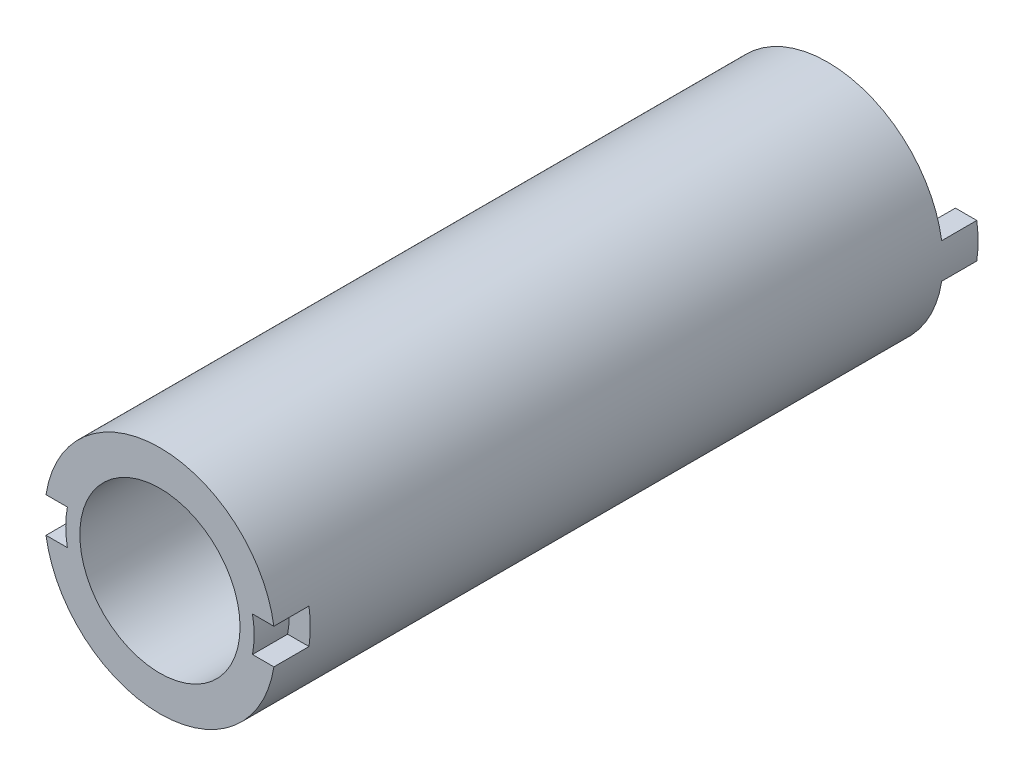
SolidWorks part; units mm, degrees
ref_plane "Front Plane" through (0, 0, 0) normal (0, 0, 1) x (1, 0, 0)
ref_plane "Top Plane" through (0, 0, 0) normal (0, 1, 0) x (1, 0, 0)
ref_plane "Right Plane" through (0, 0, 0) normal (1, 0, 0) x (0, 0, -1)
sketch "Sketch1" plane through (0, 0, 0) normal (0, 0, 1) x (1, 0, 0)
  circle A0 centre (0, 0) radius 11.4
  circle A1 centre (0, 0) radius 16.4
  dimension "D1" = 22.8
  dimension "D2" = 5
extrude "Boss-Extrude1" add sketch "Sketch1" along normal blind 95
sketch "Sketch3" plane through (0, 0, 0) normal (0, 0, -1) x (-1, 0, 0)
  line L0 (13.1647, 2.5) -> (16.2083, 2.5)
  line L1 (-16.2083, 2.5) -> (-13.1647, 2.5)
  line L3 (-16.2083, -2.5) -> (-13.1647, -2.5)
  line L5 (13.1647, -2.5) -> (16.2083, -2.5)
  line L6 (-16.4, 0) -> (-13.4, 0) construction
  arc A0 (-16.2083, 2.5) -> (-16.2083, -2.5) centre (0, 0) ccw
  arc A1 (-13.1647, 2.5) -> (-13.1647, -2.5) centre (0, 0) ccw
  arc A2 (16.2083, -2.5) -> (16.2083, 2.5) centre (0, 0) ccw
  arc A3 (13.1647, -2.5) -> (13.1647, 2.5) centre (0, 0) ccw
  circle A4 centre (0, 0) radius 16.4 construction
  dimension "D1" = 5
  dimension "D2" = 3
extrude "Boss-Extrude2" add sketch "Sketch3" along normal blind 5
sketch "Sketch4" plane through (0, 0, 95) normal (0, 0, 1) x (1, 0, 0)
  line L0 (13.1647, 2.5) -> (16.2083, 2.5)
  line L1 (-16.2083, 2.5) -> (-13.1647, 2.5)
  line L3 (-16.2083, -2.5) -> (-13.1647, -2.5)
  line L5 (13.1647, -2.5) -> (16.2083, -2.5)
  line L6 (-16.4, 0) -> (-13.4, 0) construction
  arc A0 (-16.2083, 2.5) -> (-16.2083, -2.5) centre (0, 0) ccw
  arc A1 (-13.1647, 2.5) -> (-13.1647, -2.5) centre (0, 0) ccw
  arc A2 (16.2083, -2.5) -> (16.2083, 2.5) centre (0, 0) ccw
  arc A3 (13.1647, -2.5) -> (13.1647, 2.5) centre (0, 0) ccw
  circle A4 centre (0, 0) radius 16.4 construction
  dimension "D1" = 5
  dimension "D2" = 3
extrude "Cut-Extrude1" cut sketch "Sketch4" against normal blind 5
